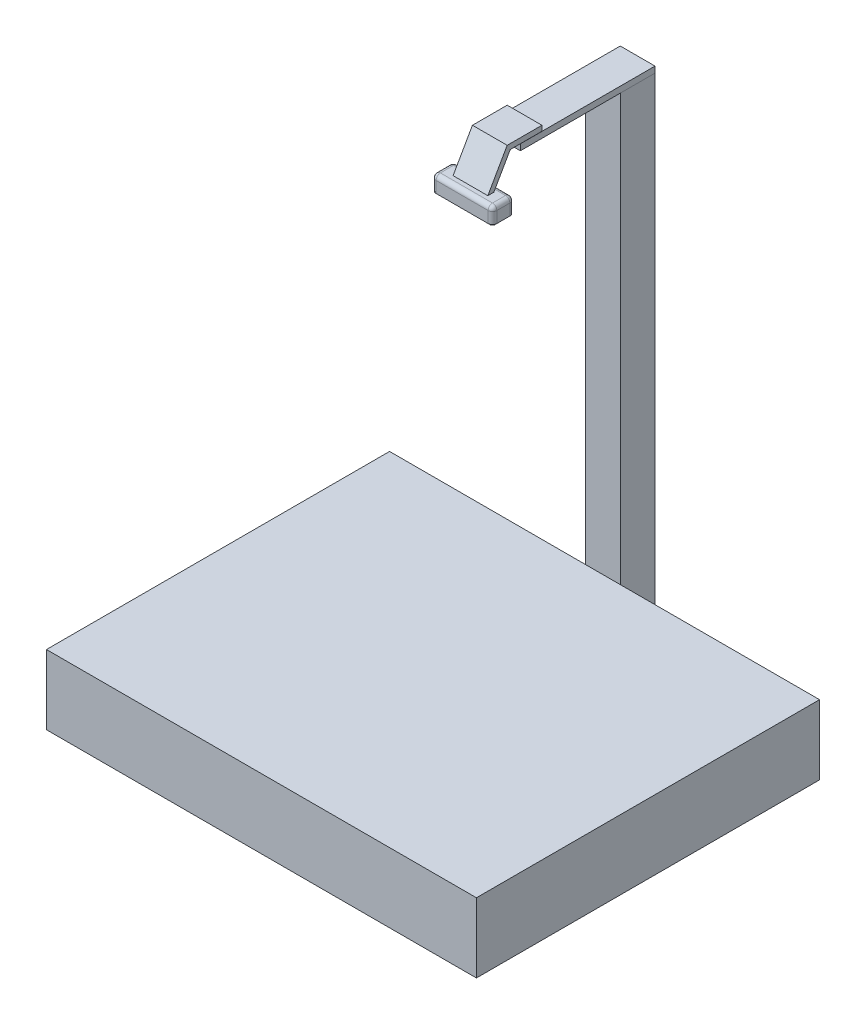
SolidWorks part; units mm, degrees
ref_plane "Front Plane" through (0, 0, 0) normal (0, 0, 1) x (1, 0, 0)
ref_plane "Top Plane" through (0, 0, 0) normal (0, 1, 0) x (1, 0, 0)
ref_plane "Right Plane" through (0, 0, 0) normal (1, 0, 0) x (0, 0, -1)
sketch "Sketch1" plane through (0, 0, 0) normal (0, 1, 0) x (1, 0, 0)
  line L1 (-247.5, -197.5) -> (247.5, -197.5)
  line L2 (-247.5, -197.5) -> (-247.5, 197.5)
  line L3 (-247.5, 197.5) -> (247.5, 197.5)
  line L4 (247.5, -197.5) -> (247.5, 197.5)
  line L5 (-247.5, -197.5) -> (247.5, 197.5) construction
  line L6 (-247.5, 197.5) -> (247.5, -197.5) construction
  point P0 (0, 0)
  dimension "D1" = 495
  dimension "D2" = 395
extrude "Boss-Extrude1" add sketch "Sketch1" along normal blind 80
sketch "Sketch2" plane through (0, 0, 0) normal (0, 1, 0) x (1, 0, 0)
  line L0 (247.5, 197.5) -> (-247.5, 197.5) construction
  line L1 (-21.9234, 237.5) -> (18.0766, 237.5)
  line L2 (-21.9234, 237.5) -> (-21.9234, 197.5)
  line L3 (-21.9234, 197.5) -> (18.0766, 197.5)
  line L4 (18.0766, 237.5) -> (18.0766, 197.5)
  line L5 (-21.9234, 237.5) -> (18.0766, 197.5) construction
  line L6 (-21.9234, 197.5) -> (18.0766, 237.5) construction
  point P0 (-1.9234, 217.5)
  dimension "D1" = 40
  dimension "D2" = 40
extrude "Boss-Extrude2" add sketch "Sketch2" along normal blind 570
sketch "Sketch3" plane through (0, 570, 0) normal (0, 1, 0) x (1, 0, 0)
  line L1 (-21.9234, 237.5) -> (18.0974, 237.5)
  line L2 (-21.9234, 237.5) -> (-21.9234, 82.5)
  line L3 (-21.9234, 82.5) -> (18.0974, 82.5)
  line L4 (18.0974, 237.5) -> (18.0974, 82.5)
  dimension "D1" = 155
extrude "Boss-Extrude3" add sketch "Sketch3" along normal blind 7
sketch "Sketch4" plane through (0, 0, 0) normal (1, 0, 0) x (0, 0, -1)
  line L0 (65.4087, 585) -> (105.4087, 585)
  line L1 (105.4087, 585) -> (105.4087, 579)
  line L2 (105.4087, 579) -> (68.8928, 579)
  line L3 (68.8928, 579) -> (50.0117, 545.9172)
  line L4 (50.0117, 545.9172) -> (53.5, 545.9172)
  line L5 (58.5, 540.9172) -> (58.5, 525.9172)
  line L6 (58.5, 525.9172) -> (33.5, 525.9172)
  line L7 (33.5, 525.9172) -> (33.5, 540.9172)
  line L8 (38.5, 545.9172) -> (43.1032, 545.9172)
  line L9 (65.4087, 585) -> (43.1032, 545.9172)
  line L10 (82.5, 577) -> (237.5, 577) construction
  line L11 (82.5, 577) -> (82.5, 570) construction
  arc A0 (33.5, 540.9172) -> (38.5, 545.9172) centre (38.5, 540.9172) cw
  arc A1 (58.5, 540.9172) -> (53.5, 545.9172) centre (53.5, 540.9172) ccw
  point P14 (54.256, 565.4586)
  dimension "D1" = 5
  dimension "D2" = 6
  dimension "D3" = 40
  dimension "D4" = 45
  dimension "D5" = 6
  dimension "D6" = 36.5159
  dimension "D7" = 2
  dimension "D8" = 20
  dimension "D9" = 0
  dimension "D10" = 25
  dimension "D11" = 24
extrude "Boss-Extrude4" add sketch "Sketch4" along normal mid plane 40 separate body contours A1 L4 L3 L2 L1 L0 L9 L8 A0 L7 L6 L5
sketch "Sketch5" plane through (0, 0, 0) normal (1, 0, 0) x (0, 0, -1)
  line L0 (58.5, 525.9172) -> (33.5, 525.9172) construction
  line L1 (58.5, 540.9172) -> (58.5, 525.9172) construction
  line L2 (50.0117, 545.9172) -> (53.5, 545.9172) construction
  line L3 (38.5, 545.9172) -> (43.1032, 545.9172) construction
  line L4 (33.5, 525.9172) -> (33.5, 540.9172) construction
  line L5 (58.5, 525.9172) -> (33.5, 525.9172)
  line L6 (58.5, 540.9172) -> (58.5, 525.9172)
  line L7 (50.0117, 545.9172) -> (53.5, 545.9172)
  line L8 (38.5, 545.9172) -> (43.1032, 545.9172)
  line L9 (33.5, 525.9172) -> (33.5, 540.9172)
  line L10 (43.1032, 545.9172) -> (50.0117, 545.9172)
  arc A0 (58.5, 540.9172) -> (53.5, 545.9172) centre (53.5, 540.9172) ccw construction
  arc A1 (38.5, 545.9172) -> (33.5, 540.9172) centre (38.5, 540.9172) ccw construction
  arc A2 (58.5, 540.9172) -> (53.5, 545.9172) centre (53.5, 540.9172) ccw
  arc A3 (38.5, 545.9172) -> (33.5, 540.9172) centre (38.5, 540.9172) ccw
extrude "Boss-Extrude5" add sketch "Sketch5" along normal mid plane 70
fillet "Fillet1" radius 5 10 edges at (-35, 533.4172, -33.5) (-35, 544.4527, -34.9645) (-35, 545.9172, -46) (-35, 544.4527, -57.0355) (35, 533.4172, -33.5) (35, 544.4527, -34.9645) (35, 545.9172, -46) (35, 544.4527, -57.0355) (-35, 533.4172, -58.5) (35, 533.4172, -58.5)
chamfer "Chamfer1" distance 2 angle 45 8 edges at (0, 525.9172, -33.5) (33.5355, 525.9172, -34.9645) (-33.5355, 525.9172, -34.9645) (35, 525.9172, -46) (-35, 525.9172, -46) (33.5355, 525.9172, -57.0355) (-33.5355, 525.9172, -57.0355) (0, 525.9172, -58.5)
